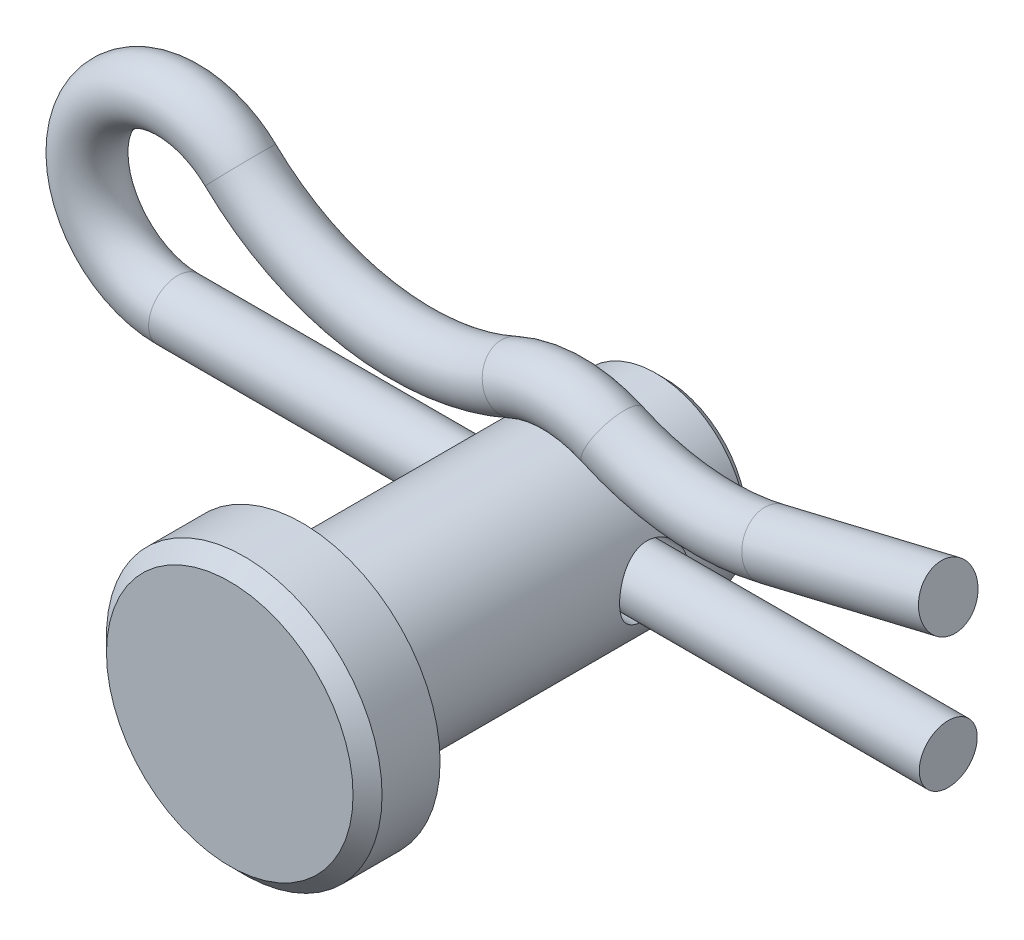
SolidWorks part; units mm, degrees
ref_plane "Front" through (0, 0, 0) normal (0, 0, 1) x (1, 0, 0)
ref_plane "Top" through (0, 0, 0) normal (0, 1, 0) x (1, 0, 0)
ref_plane "Right" through (0, 0, 0) normal (1, 0, 0) x (0, 0, -1)
sketch "Sketch1" plane through (0, 0, 0) normal (0, 0, 1) x (1, 0, 0)
  circle A0 centre (0, 0) radius 3.175
  point P3 (0, 3.175)
  point P4 (0, -3.175)
  dimension "dia" = 6.35
extrude "Extrude1" add sketch "Sketch1" along normal mid plane 12.7
sketch "Sketch2" plane through (0, 0, 6.35) normal (0, 0, 1) x (1, 0, 0)
  circle A0 centre (0, 0) radius 4.826
  dimension "head dia" = 9.652
extrude "Extrude2" add sketch "Sketch2" along normal blind 2.54
chamfer "Chamfer1" distance 0.508 angle 45 1 edges at (4.826, 0, 8.89)
sketch "Sketch3" plane through (0, 0, 0) normal (1, 0, 0) x (0, 0, -1)
  line L0 (-6.35, -3.175) -> (-6.35, 3.175) construction
  circle A0 centre (2.7781, 0) radius 1.1906
  point P2 (1.5875, 0)
  dimension "hole dia" = 2.3813
  dimension "useable Lg" = 7.9375
extrude "Extrude3" cut sketch "Sketch3" against normal through all and the other way through all
chamfer "Chamfer2" distance 0.3175 angle 45 1 edges at (3.175, 0, -6.35)
ref_plane "Plane1" through (0, 0, -2.7781) normal (0, 0, 1) x (1, 0, 0)
sketch "Sketch6" plane through (0, 0, -2.7781) normal (0, 0, 1) x (1, 0, 0)
  line L0 (13.4937, 0) -> (-13.4937, 0)
  line L1 (7.306, 3.2847) -> (13.4937, 4.7625)
  line L2 (-13.4937, 3.175) -> (-13.4937, 6.35) construction
  arc A0 (-13.4937, 0) -> (-11.293, 5.4635) centre (-13.4937, 3.175) cw
  arc A1 (1.7284, 3.818) -> (-1.7284, 3.818) centre (0, 0) ccw
  circle A2 centre (0, 0) radius 1.016 construction
  arc A3 (-1.7284, 3.818) -> (-11.293, 5.4635) centre (-5.2963, 11.6993) cw
  circle A4 centre (0, 4.191) radius 1.016 construction
  circle A5 centre (0, 0) radius 3.175 construction
  arc A6 (1.7284, 3.818) -> (7.306, 3.2847) centre (5.2963, 11.6993) ccw
  point P2 (-5.2963, 3.048)
  point P9 (-13.4937, 4.7625)
  point P18 (-16.6687, 3.175)
  point P22 (-13.4937, 6.35)
  point P23 (0, 1.016)
  dimension "pin dia" = 2.032
  dimension "D2" = 6.35
  dimension "pin Lg" = 30.1625
  dimension "D1" = 3.048
ref_plane "Plane2" through (13.4937, 0, -2.7781) normal (-1, 0, 0) x (0, 0, 1)
sketch "Sketch7" plane through (13.4937, 0, -2.7781) normal (-1, 0, 0) x (0, 0, 1)
  circle A0 centre (0, 0) radius 1.016
sweep "Sweep1" add profiles "Sketch7" path "Sketch6"
sketch "Sketch8" plane through (0, 0, 0) normal (1, 0, 0) x (0, 0, -1)
  line L0 (-8.89, 4.318) -> (-8.89, -4.318) construction
  line L1 (-8.382, -4.826) -> (-6.35, -4.826) construction
  line L2 (6.35, -2.8575) -> (6.35, 2.8575) construction
  line L3 (1.5875, 7.366) -> (2.7781, 7.366) construction
  line L4 (2.7781, 3.175) -> (2.7781, 6.35) construction
  arc A0 (3.7941, 6.35) -> (1.7621, 6.35) centre (2.7781, 6.35) ccw construction
  point P0 (-8.89, 4.826)
  point P1 (-6.35, 4.826)
  point P5 (6.35, 3.175)
  point P8 (-8.89, -4.826)
  point P9 (6.35, -3.175)
  point P12 (1.5875, 7.366)
equation "\"D1@Chamfer1\" = \"head ht@Extrude2\" * .2"
equation "\"D1@Chamfer2\" = \"dia@Sketch1\" * .05"
equation "\"D2@Sketch6\" = \"dia@Sketch1\" * 1"
equation "\"D1@Sketch6\" = \"pin dia@Sketch6\" * 1.5"
